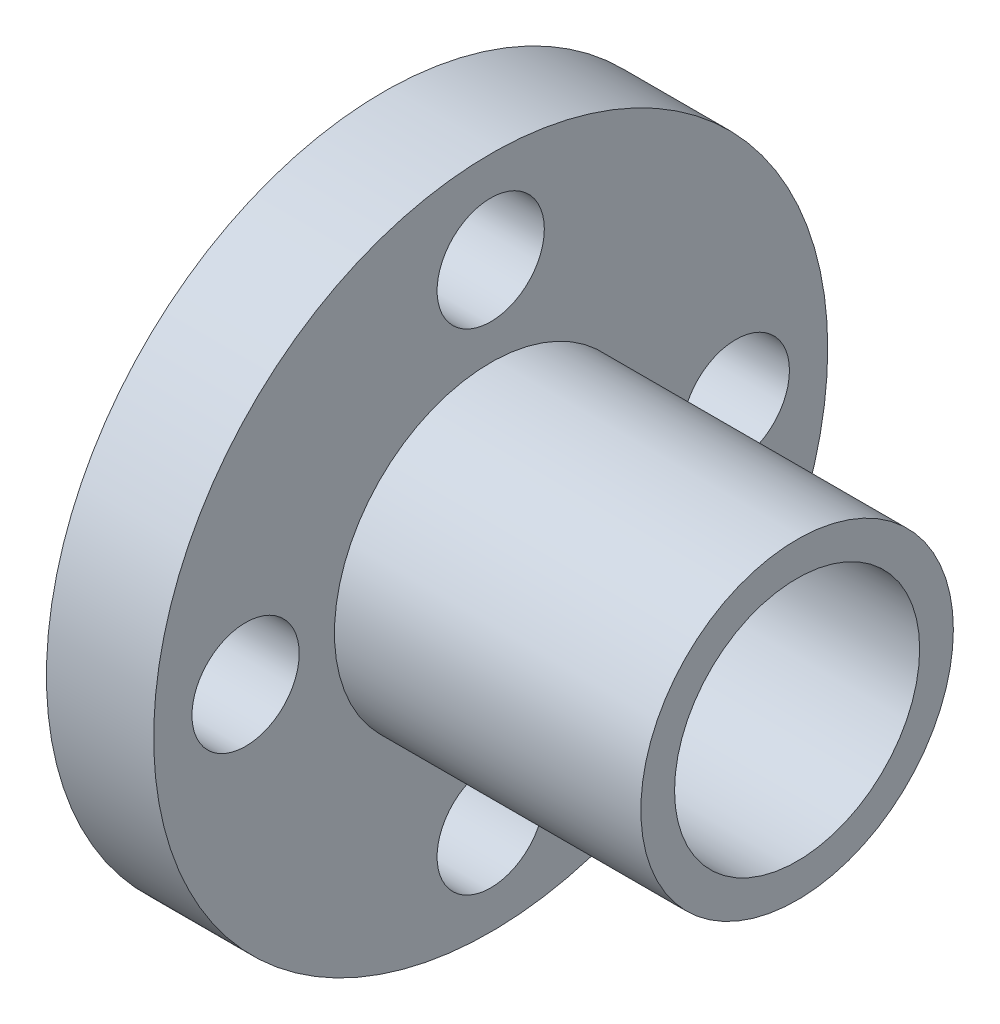
SolidWorks part; units mm, degrees
ref_plane "前视基准面" through (0, 0, 0) normal (0, 0, 1) x (1, 0, 0)
ref_plane "上视基准面" through (0, 0, 0) normal (0, 1, 0) x (1, 0, 0)
ref_plane "右视基准面" through (0, 0, 0) normal (1, 0, 0) x (0, 0, -1)
sketch "草图1" plane through (0, 0, 0) normal (1, 0, 0) x (0, 0, -1)
  circle A0 centre (0, 0) radius 11
  circle A1 centre (0, 0) radius 4
  circle A2 centre (0, 0) radius 8 construction
  circle A3 centre (0, 8) radius 1.75
  circle A4 centre (8, 0) radius 1.75
  circle A5 centre (0, -8) radius 1.75
  circle A6 centre (-8, 0) radius 1.75
  point P16 (0, 0)
  dimension "D1" = 22
  dimension "D2" = 8
  dimension "D3" = 16
  dimension "D4" = 3.5
  dimension "D5" = 4
extrude "凸台-拉伸1" add sketch "草图1" along normal blind 3.5
sketch "草图2" plane through (3.5, 0, 0) normal (1, 0, 0) x (0, 0, -1)
  circle A0 centre (0, 0) radius 5.1
  circle A1 centre (0, 0) radius 4
  dimension "D1" = 10.2
extrude "凸台-拉伸2" add sketch "草图2" along normal blind 10 and the other way blind 5
